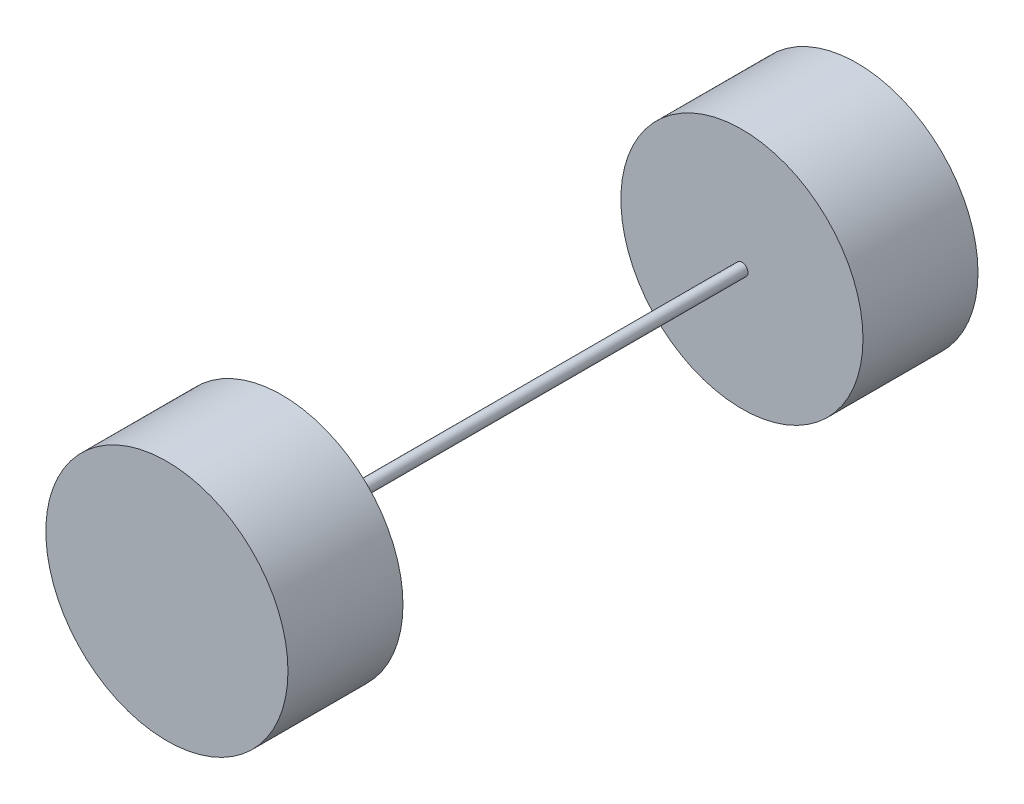
SolidWorks part; units mm, degrees
ref_plane "Front Plane" through (0, 0, 0) normal (0, 0, 1) x (1, 0, 0)
ref_plane "Top Plane" through (0, 0, 0) normal (0, 1, 0) x (1, 0, 0)
ref_plane "Right Plane" through (0, 0, 0) normal (1, 0, 0) x (0, 0, -1)
sketch "Sketch1" plane through (0, 0, 0) normal (0, 0, 1) x (1, 0, 0)
  circle A0 centre (0, 0) radius 20
  dimension "D1" = 40
extrude "Boss-Extrude1" add sketch "Sketch1" along normal blind 19
sketch "Sketch2" plane through (0, 0, 19) normal (0, 0, 1) x (1, 0, 0)
  circle A0 centre (0, 0) radius 1
  dimension "D1" = 2
extrude "Boss-Extrude2" add sketch "Sketch2" along normal blind 76
sketch "Sketch3" plane through (0, 0, 95) normal (0, 0, 1) x (1, 0, 0)
  circle A1 centre (0, 0) radius 20
  circle A2 centre (0, 0) radius 20
  dimension "D1" = 0
extrude "Boss-Extrude3" add sketch "Sketch3" along normal blind 19
